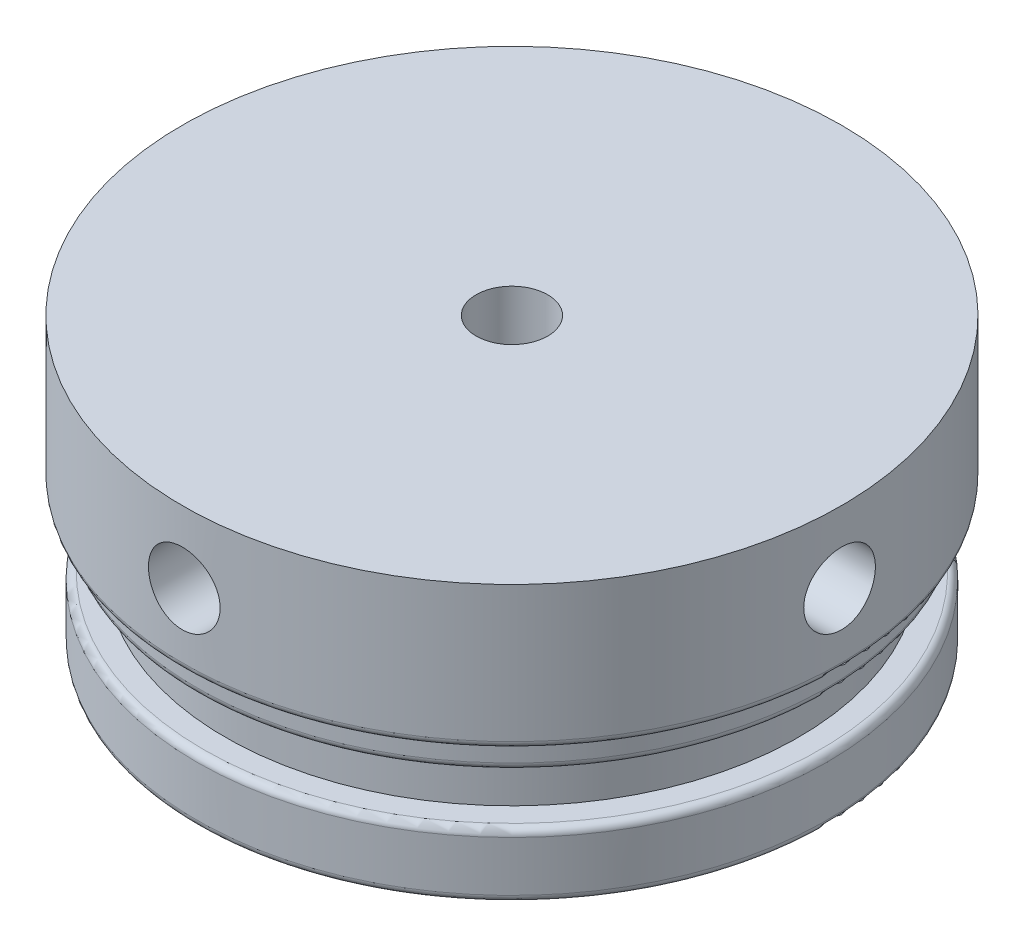
SolidWorks part; units mm, degrees
material "6061-T6 (SS)"
ref_plane "정면" through (0, 0, 0) normal (0, 0, 1) x (1, 0, 0)
ref_plane "윗면" through (0, 0, 0) normal (0, 1, 0) x (1, 0, 0)
ref_plane "우측면" through (0, 0, 0) normal (1, 0, 0) x (0, 0, -1)
sketch "스케치2" plane through (0, 0, 0) normal (0, 0, 1) x (1, 0, 0)
  line L0 (0, 0) -> (0, 20)
  line L1 (0, 20) -> (23, 20)
  line L2 (23, 20) -> (23, 10)
  line L3 (23, 10) -> (22, 10)
  line L4 (22, 10) -> (22, 8)
  line L5 (22, 8) -> (20, 8)
  line L6 (20, 8) -> (20, 4.5)
  line L7 (20, 4.5) -> (22, 4.5)
  line L8 (22, 4.5) -> (22, 0)
  line L9 (22, 0) -> (0, 0)
  point P3 (0, 0)
  dimension "D1" = 20
  dimension "D2" = 23
  dimension "D3" = 22
  dimension "D4" = 1
  dimension "D5" = 2
  dimension "D6" = 2
  dimension "D7" = 3.5
revolve "회전1" add sketch "스케치2" angle 360 about L0
ref_plane "평면1" through (-23, 0, 0) normal (-1, 0, 0) x (0, 0, 1)
sketch "스케치3" plane through (-23, 0, 0) normal (-1, 0, 0) x (0, 0, 1)
  line L0 (0, 10) -> (0, 15)
  line L1 (-22, 10) -> (22, 10) construction
  circle A0 centre (0, 15) radius 2.5
  dimension "D1" = 5
extrude "컷-돌출1" cut sketch "스케치3" against normal blind 6
ref_plane "평면2" through (0, 0, -23) normal (0, 0, -1) x (-1, 0, 0)
sketch "스케치4" plane through (0, 0, -23) normal (0, 0, -1) x (-1, 0, 0)
  line L0 (0, 10) -> (0, 15)
  line L1 (-22, 10) -> (22, 10) construction
  circle A0 centre (0, 15) radius 2.5
  dimension "D1" = 5
extrude "컷-돌출2" cut sketch "스케치4" against normal blind 6
ref_plane "평면3" through (23, 0, 0) normal (1, 0, 0) x (0, 0, -1)
sketch "스케치5" plane through (23, 0, 0) normal (1, 0, 0) x (0, 0, -1)
  line L0 (0, 10) -> (0, 15)
  line L1 (-22, 10) -> (22, 10) construction
  circle A0 centre (0, 15) radius 2.5
  dimension "D1" = 5
extrude "컷-돌출3" cut sketch "스케치5" against normal blind 6
ref_plane "평면4" through (0, 0, 23) normal (0, 0, 1) x (1, 0, 0)
sketch "스케치6" plane through (0, 0, 23) normal (0, 0, 1) x (1, 0, 0)
  line L0 (0, 10) -> (0, 15)
  line L1 (-22, 10) -> (22, 10) construction
  circle A0 centre (0, 15) radius 2.5
  dimension "D1" = 5
extrude "컷-돌출4" cut sketch "스케치6" against normal blind 6
sketch "스케치7" plane through (0, 20, 0) normal (0, 1, 0) x (1, 0, 0)
  circle A0 centre (0, 0) radius 2.5
  dimension "D1" = 5
extrude "컷-돌출5" cut sketch "스케치7" against normal blind 6
fillet "필렛1" radius 0.5 1 edges at (0, 8, -22)
fillet "필렛2" radius 0.5 1 edges at (0, 4.5, -22)
fillet "필렛3" radius 0.5 1 edges at (0, 0, -22)
fillet "필렛4" radius 0.5 1 edges at (0, 10, -23)
